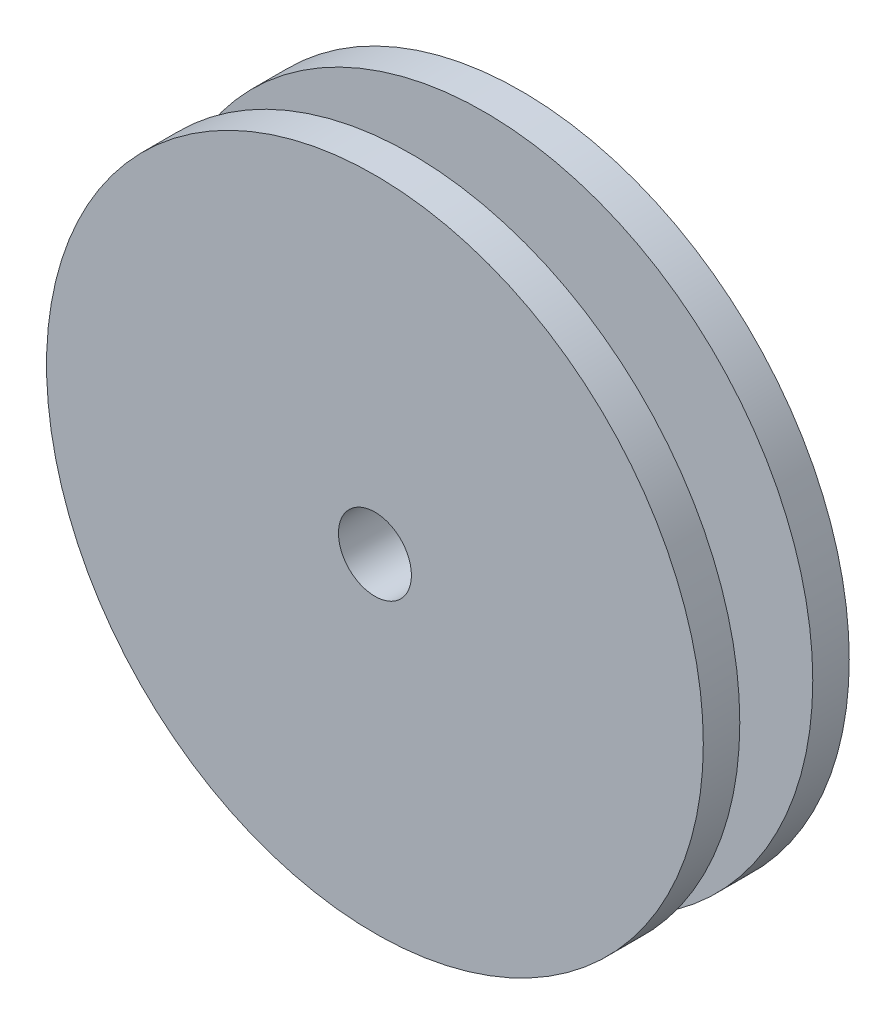
SolidWorks part; units mm, degrees
ref_plane "前视基准面" through (0, 0, 0) normal (0, 0, 1) x (1, 0, 0)
ref_plane "上视基准面" through (0, 0, 0) normal (0, 1, 0) x (1, 0, 0)
ref_plane "右视基准面" through (0, 0, 0) normal (1, 0, 0) x (0, 0, -1)
sketch "草图1" plane through (0, 0, 0) normal (0, 0, 1) x (1, 0, 0)
  circle A0 centre (0, 0) radius 13.5
  circle A1 centre (0, 0) radius 2.774
  dimension "D1" = 27
extrude "凸台-拉伸1" add sketch "草图1" along normal blind 6 contours A0
sketch "草图3" plane through (0, 0, 0) normal (0, 0, 1) x (1, 0, 0)
  circle A0 centre (0, 0) radius 1.5
  dimension "D1" = 3
extrude "切除-拉伸2" cut sketch "草图3" along normal through all contours A0
ref_plane "基准面4" through (0, 0, 4.5) normal (0, 0, 1) x (1, 0, 0)
sketch "草图4" plane through (0, 0, 4.5) normal (0, 0, 1) x (1, 0, 0)
  circle A0 centre (0, 0) radius 13.5 construction
  circle A1 centre (0, 0) radius 13.5
  circle A2 centre (0, 0) radius 9
  dimension "D1" = 18
extrude "切除-拉伸3" cut sketch "草图4" against normal blind 3
